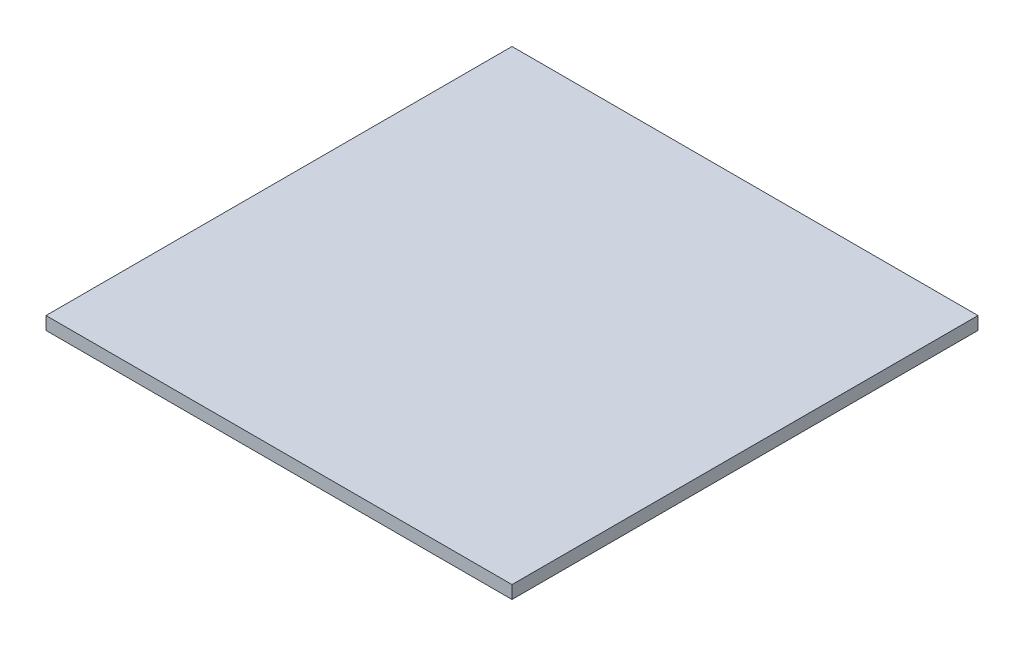
SolidWorks part; units mm, degrees
ref_plane "Front Plane" through (0, 0, 0) normal (0, 0, 1) x (1, 0, 0)
ref_plane "Top Plane" through (0, 0, 0) normal (0, 1, 0) x (1, 0, 0)
ref_plane "Right Plane" through (0, 0, 0) normal (1, 0, 0) x (0, 0, -1)
sketch "Sketch1" plane through (0, 0, 0) normal (0, 0, 1) x (1, 0, 0)
  line L1 (457.2, -12.7) -> (-457.2, -12.7)
  line L2 (457.2, -12.7) -> (457.2, 12.7)
  line L3 (457.2, 12.7) -> (-457.2, 12.7)
  line L4 (-457.2, -12.7) -> (-457.2, 12.7)
  line L5 (457.2, -12.7) -> (-457.2, 12.7) construction
  line L6 (457.2, 12.7) -> (-457.2, -12.7) construction
  point P0 (0, 0)
  dimension "D1" = 25.4
  dimension "D2" = 914.4
extrude "Boss-Extrude1" add sketch "Sketch1" along normal mid plane 914.4
